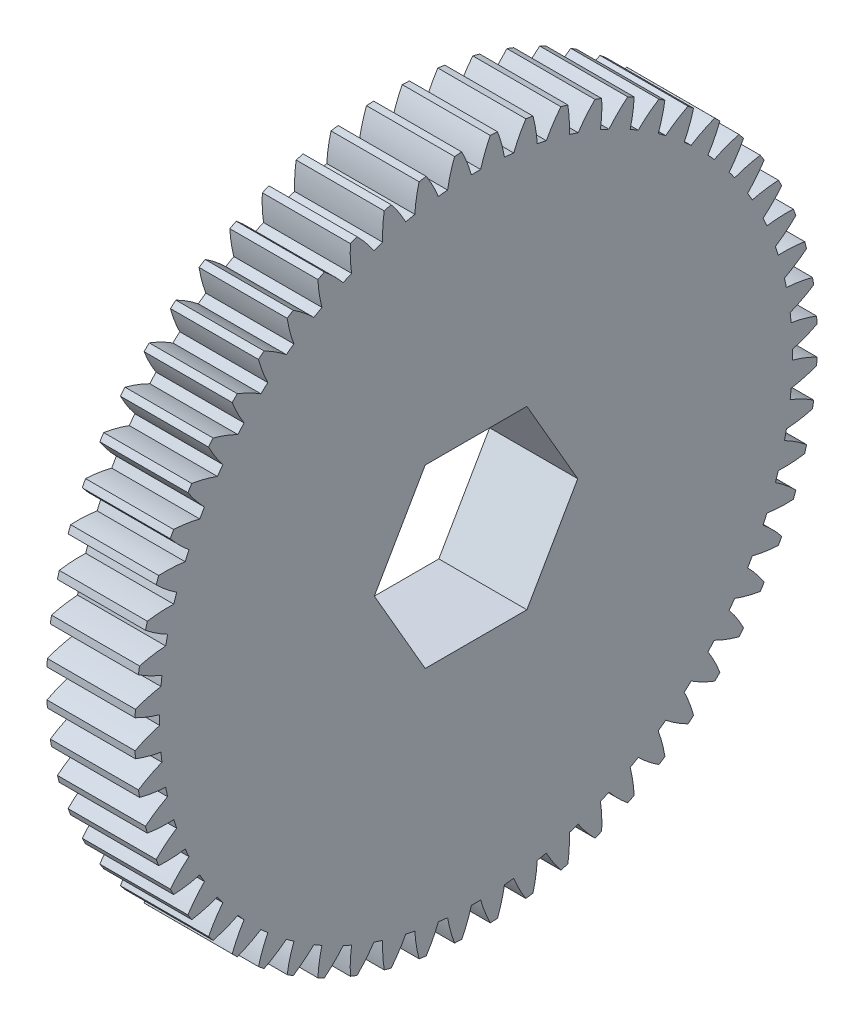
SolidWorks part; units mm, degrees
ref_plane "Plane1" through (0, 0, 0) normal (0, 0, 1) x (1, 0, 0)
ref_plane "Plane2" through (0, 0, 0) normal (0, 1, 0) x (1, 0, 0)
ref_plane "Plane3" through (0, 0, 0) normal (1, 0, 0) x (0, 0, -1)
other "Configuration Table"
sketch "HoldingSke" plane through (0, 0, 0) normal (0, 1, 0) x (1, 0, 0)
  line L0 (0, 0) -> (406.4, -703.9054)
  line L1 (-15, 0) -> (100, 0) construction
  line L2 (0, 0) -> (-2.1039, 2.3779)
  line L3 (0, 0) -> (-11.863, 4.5341)
  line L4 (0, 0) -> (4.318, 7.479)
  line L5 (0, 0) -> (-47.5972, -17.7524)
  line L6 (0, 0) -> (-4.2111, -2.8413)
  line L7 (-2.1039, 2.3779) -> (8.8308, 51.9871)
  line L8 (-76.2, 54.61) -> (-75.184, 54.61)
  line L9 (-71.009, 38.7566) -> (-53.1078, 45.2721)
  line L10 (-76.2, 71.12) -> (104.1128, 71.12)
  line L11 (0, 0) -> (-5.08, 0)
  line L12 (-76.2, 101.6) -> (-76.1716, 101.6)
  line L13 (24.9733, 27.94) -> (52.9518, 28.4284)
  line L14 (24.9733, 27.94) -> (25.0241, 27.9398)
  line L15 (24.9733, 27.94) -> (100.4021, 29.52)
  circle A0 centre (0, 0) radius 0.3969
  circle A1 centre (0, 0) radius 22.8092
  circle A2 centre (0, 0) radius 38.1
  circle A3 centre (0, 0) radius 0.3969
  dimension "MHD" = 45.6184
  dimension "Hub_dia" = 76.2
  dimension "Bore" = 0.7937
  dimension "MBD" = 0.7937
  dimension "Num_teeth" = 60
  dimension "Pitch" = 812.8
  dimension "Overall_len" = 50.8
  dimension "Show_teeth" = 60
  dimension "Thickness" = 5.08
  dimension "OAL" = 50.8001
  dimension "T_dim" = 1.016
  dimension "Ap" = 20
  dimension "H" = 19.05
  dimension "Pitch_radius" = 180.3128
  dimension "Width" = 5.08
  dimension "Backlash" = 0.0284
  dimension "Addendum_fac" = 1
  dimension "Dedendum_fac" = 1.2
  dimension "Clearance_fac" = 0.2
  dimension "Dedendum_add" = 0.0508
sketch "BasProSke" plane through (0, 0, 0) normal (0, 1, 0) x (1, 0, 0)
  line L0 (-10, 0) -> (60, 0) construction
  line L1 (0, 0) -> (0, 24.6063)
  line L2 (0, 0) -> (6.35, 0)
  line L3 (6.35, 0) -> (6.35, 24.6062)
  line L4 (6.35, 24.6062) -> (0, 24.6063)
  dimension "Thickness" = 6.35
  dimension "Diameter" = 49.2125
revolve "Base-Revolve" add sketch "BasProSke" angle 360 about L0
sketch "TooCutSke" plane through (0, 0, 0) normal (1, 0, 0) x (0, 0, -1)
  line L1 (0, 0) -> (0, 107) construction
  line L2 (0, 0) -> (-0.6731, 23.803) construction
  line L3 (0, 0) -> (-2.4918, 47.5459) construction
  line L4 (-0.6731, 23.803) -> (-1.2459, 23.773) construction
  arc A0 (0.3357, 22.8067) -> (-0.3357, 22.8067) centre (0, 0) ccw
  arc A1 (1.0415, 24.6096) -> (-1.0415, 24.6096) centre (0, 0) ccw
  circle A2 centre (0, 0) radius 23.8125 construction
  circle A3 centre (0, 0) radius 22.3764 construction
  arc A4 (-0.3357, 22.8067) -> (-1.0415, 24.6096) centre (-9.5122, 20.2539) ccw
  arc A5 (1.0415, 24.6096) -> (0.3357, 22.8067) centre (9.5122, 20.2539) ccw
  dimension "Root_dia" = 45.6184
  dimension "Overcut_dia" = 49.2633
  dimension "Pitch_dia" = 47.625
  dimension "Base_dia" = 44.7529
  dimension "Flank_rad" = 9.525
  dimension "Half_ang" = 3
  dimension "Half_CT" = 0.5736
extrude "ToothCut" cut sketch "TooCutSke" along normal through all
fillet "Breaks" [suppressed] radius 0.0159
fillet "RootFillets" [suppressed] radius 0.2095
pattern_circular "TeethCuts" count 60 every 6 about axis through (-10, 0, 0) along (1, 0, 0) of "ToothCut", "RootFillets", "Breaks"
sketch "HubNeaOneSke" plane through (0, 0, 0) normal (-1, 0, 0) x (0, 0, 1)
  circle A0 centre (0, 0) radius 22.8092
  dimension "Diameter" = 45.6184
extrude "HubNearOne" [suppressed] add sketch "HubNeaOneSke" along normal blind 44.4501
sketch "HubNeaBotSke" plane through (0, 0, 0) normal (-1, 0, 0) x (0, 0, 1)
  circle A0 centre (0, 0) radius 22.8092
  dimension "Diameter" = 45.6184
extrude "HubNearBoth" [suppressed] add sketch "HubNeaBotSke" along normal blind 22.225
ref_plane "FarPln" through (6.35, 0, 0) normal (1, 0, 0) x (0, 0, -1)
sketch "HubFarSke" plane through (6.35, 0, 0) normal (1, 0, 0) x (0, 0, -1)
  circle A0 centre (0, 0) radius 22.8092
  dimension "Diameter" = 45.6184
extrude "HubFar" [suppressed] add sketch "HubFarSke" along normal blind 22.225
sketch "BorSke" plane through (0, 0, 0) normal (1, 0, 0) x (0, 0, -1)
  circle A0 centre (0, 0) radius 6.35
  dimension "Diameter" = 12.7
extrude "Bore" [suppressed] cut sketch "BorSke" along normal mid plane 101.6001
sketch "KeySke" plane through (0, 0, 0) normal (1, 0, 0) x (0, 0, -1)
  line L0 (-0.127, 0) -> (-0.127, 0.6191)
  line L1 (-0.127, 0.6191) -> (0.127, 0.6191)
  line L2 (0.127, 0.6191) -> (0.127, 0)
  line L3 (0, 0) -> (0, 34) construction
  line L4 (-0.127, 0) -> (0.127, 0)
  dimension "Offset" = 0.6191
  dimension "Width" = 0.254
extrude "Keyway" [suppressed] cut sketch "KeySke" along normal mid plane 101.6001
pattern_circular "Keyway2" [suppressed] count 2 every 90 about axis through (-10, 0, 0) along (1, 0, 0)
sketch "Sketch3" plane through (6.35, 0, 0) normal (1, 0, 0) x (0, 0, -1)
  line L1 (-3.6662, 6.35) -> (-7.3323, 0)
  line L2 (-7.3323, 0) -> (-3.6662, -6.35)
  line L3 (-3.6662, -6.35) -> (3.6662, -6.35)
  line L4 (3.6662, -6.35) -> (7.3323, 0)
  line L5 (7.3323, 0) -> (3.6662, 6.35)
  line L6 (3.6662, 6.35) -> (-3.6662, 6.35)
  circle A0 centre (0, 0) radius 6.35 construction
  point P1 (-3.6662, 6.35)
extrude "Cut-Extrude2" cut sketch "Sketch3" against normal through all
equation "' \"Pitch@HoldingSke\" = 4"
equation "' \"Num_teeth@HoldingSke\" = 12"
equation "' \"Ap@HoldingSke\" =  20"
equation "' \"Ap@HoldingSke\" = 20"
equation "' \"Width@HoldingSke\" = 0.5"
equation "' \"Hub_dia@HoldingSke\"= 1"
equation "' \"Hub_dia@HoldingSke\" = 1"
equation "' \"Overall_len@HoldingSke\" = 1.0"
equation "' \"Bore@HoldingSke\" = 0.75"
equation "' \"T_dim@HoldingSke\" = 0.85"
equation "' \"Width@KeySke\" = 0.25"
equation "' \"Show_teeth@HoldingSke\" = 13"
equation "' \"Backlash@HoldingSke\" = 0.009"
equation "' \"Addendum_fac@HoldingSke\" = 1.0"
equation "' \"Dedendum_fac@HoldingSke\" = 1.25"
equation "' \"Dedendum_add@HoldingSke\" = 0.00005"
equation "' \"Clearance_fac@HoldingSke\" = 0.25"
equation "' \"Pitch@HoldingSke\" = 0.5"
equation "' \"Num_teeth@HoldingSke\" = 23"
equation "' \"Show_teeth@HoldingSke\" = 23"
equation "' \"Backlash@HoldingSke\" = 0.0375"
equation "\"Overcut_dia@TooCutSke\" = (\"Num_teeth@HoldingSke\" + 2 * \"Addendum_fac@HoldingSke\") / \"Pitch@HoldingSke\" + 0.002"
equation "\"Pitch_dia@TooCutSke\" = \"Num_teeth@HoldingSke\" / \"Pitch@HoldingSke\""
equation "\"Base_dia@TooCutSke\" = \"Num_teeth@HoldingSke\" / \"Pitch@HoldingSke\" * cos((\"Ap@HoldingSke\"  * 3.14159265 / 180))"
equation "\"Root_dia@TooCutSke\" = (\"Num_teeth@HoldingSke\" + 2) / \"Pitch@HoldingSke\" - 2 * (\"Addendum_fac@HoldingSke\" + \"Dedendum_fac@HoldingSke\") / \"Pitch@HoldingSke\" - \"Dedendum_add@HoldingSke\" * 2"
equation "\"Half_ang@TooCutSke\" = 180 / \"Num_teeth@HoldingSke\""
equation "\"Half_CT@TooCutSke\" = \"Num_teeth@HoldingSke\" / \"Pitch@HoldingSke\" * sin((3.14159265 / 2 / \"Num_teeth@HoldingSke\")) / 2 - 7 * \"Backlash@HoldingSke\" / 4"
equation "\"Flank_rad@TooCutSke\" = \"Num_teeth@HoldingSke\" / \"Pitch@HoldingSke\" / 5"
equation "\"Radius@RootFillets\" = \"Clearance_fac@HoldingSke\" / \"Pitch@HoldingSke\" + \"Dedendum_add@HoldingSke\""
equation "\"Break_rad@Breaks\" = 0.02 / \"Pitch@HoldingSke\""
equation "\"Thickness@HoldingSke\" = \"Width@HoldingSke\""
equation "\"OAL@HoldingSke\" = \"Thickness@HoldingSke\""
equation "\"MHD@HoldingSke\" = (\"Num_teeth@HoldingSke\" + 2) / \"Pitch@HoldingSke\" - 2 * (\"Addendum_fac@HoldingSke\" + \"Dedendum_fac@HoldingSke\")  / \"Pitch@HoldingSke\" - \"Dedendum_add@HoldingSke\" * 2"
equation "\"MBD@HoldingSke\" = (\"Num_teeth@HoldingSke\" + 2) / \"Pitch@HoldingSke\" - 2 * (\"Addendum_fac@HoldingSke\" + \"Dedendum_fac@HoldingSke\")  / \"Pitch@HoldingSke\" - \"Dedendum_add@HoldingSke\" * 2 - 0.002"
equation "\"MHD@HoldingSke\" = ((sgn( \"MHD@HoldingSke\" - \"Hub_dia@HoldingSke\" )-1)*( \"MHD@HoldingSke\" - \"Hub_dia@HoldingSke\" ))/-2+ \"Hub_dia@HoldingSke\""
equation "\"MBD@HoldingSke\" = ((sgn( \"MBD@HoldingSke\" - \"Bore@HoldingSke\" )-1)*( \"MBD@HoldingSke\" - \"Bore@HoldingSke\" ))/-2+ \"Bore@HoldingSke\""
equation "\"OAL@HoldingSke\" = ((sgn( \"OAL@HoldingSke\" - \"Overall_len@HoldingSke\" )+1)*( \"OAL@HoldingSke\" - \"Overall_len@HoldingSke\" ))/2 + \"Overall_len@HoldingSke\" + 0.000002"
equation "\"Num_teeth@TeethCuts\" = int( \"Show_teeth@HoldingSke\" ) + 1"
equation "\"Num_teeth@TeethCuts\" = ((sgn( \"Num_teeth@TeethCuts\" - \"Num_teeth@HoldingSke\" )-1)*( \"Num_teeth@TeethCuts\" - \"Num_teeth@HoldingSke\" ))/-2+ \"Num_teeth@HoldingSke\""
equation "\"Num_teeth@TeethCuts\" = ((sgn( \"Num_teeth@TeethCuts\" - 2.0)+1)*( \"Num_teeth@TeethCuts\" - 2.0))/2 +2.0"
equation "\"Angle@TeethCuts\" = 360.0 / \"Num_teeth@HoldingSke\""
equation "\"Diameter@BasProSke\" = (\"Num_teeth@HoldingSke\" + 2 * \"Addendum_fac@HoldingSke\") / \"Pitch@HoldingSke\""
equation "\"Thickness@BasProSke\"=.25"
equation "' \"Fillet_rad@BasProSke\" =  \"Thickness@HoldingSke\" * 0.05"
equation "' \"Fillet_rad@BasProSke\" = \"Thickness@HoldingSke\" * 0.05"
equation "\"MHD@HoldingSke\" = ((sgn( \"MHD@HoldingSke\" - \"Root_dia@TooCutSke\" )-1)*( \"MHD@HoldingSke\" - \"Root_dia@TooCutSke\" ))/-2+ \"Root_dia@TooCutSke\""
equation "\"Diameter@HubNeaOneSke\" = \"MHD@HoldingSke\""
equation "\"Length@HubNearOne\" = \"OAL@HoldingSke\" - \"Thickness@BasProSke\""
equation "\"Diameter@HubNeaBotSke\" = \"MHD@HoldingSke\""
equation "\"Length@HubNearBoth\" = ( \"OAL@HoldingSke\" - \"Thickness@BasProSke\" ) / 2.0"
equation "\"Thickness@FarPln\" = \"Thickness@BasProSke\""
equation "\"Diameter@HubFarSke\" = \"MHD@HoldingSke\""
equation "\"Length@HubFar\" = ( \"OAL@HoldingSke\" - \"Thickness@BasProSke\" ) / 2.0"
equation "\"Diameter@BorSke\"=0.5in"
equation "\"D1@Bore\" = \"OAL@HoldingSke\" * 2.0"
equation "\"D1@Keyway\" = \"OAL@HoldingSke\" * 2.0"
equation "\"Offset@KeySke\" = \"T_dim@HoldingSke\" - \"MBD@HoldingSke\" / 2.0"
